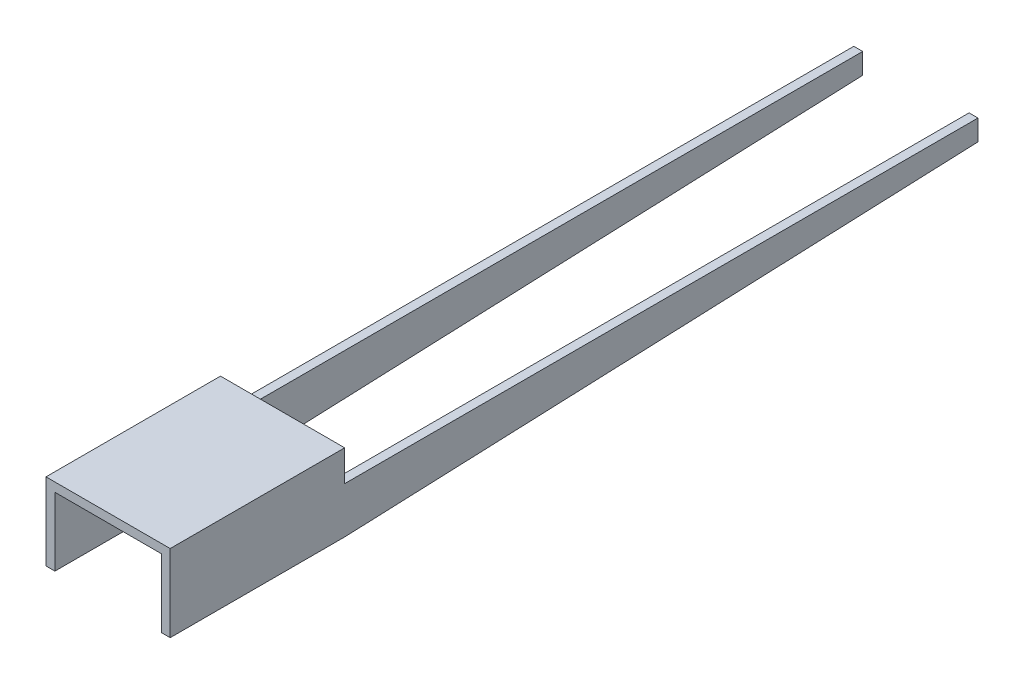
SolidWorks part; units mm, degrees
ref_plane "Front Plane" through (0, 0, 0) normal (0, 0, 1) x (1, 0, 0)
ref_plane "Top Plane" through (0, 0, 0) normal (0, 1, 0) x (1, 0, 0)
ref_plane "Right Plane" through (0, 0, 0) normal (1, 0, 0) x (0, 0, -1)
sketch "Sketch1" plane through (0, 0, 0) normal (0, 0, 1) x (1, 0, 0)
  line L0 (-30, 0) -> (-25.7, 0)
  line L5 (-25.7, 0) -> (-25.7, 20.7)
  line L6 (-25.7, 20.7) -> (25.7, 20.7)
  line L7 (25.7, 20.7) -> (25.7, 0)
  line L8 (25.7, 0) -> (30, 0)
  line L9 (30, 0) -> (30, 25)
  line L10 (30, 25) -> (-30, 25)
  line L11 (-30, 25) -> (-30, 0)
  point P9 (0, 20.7)
  dimension "D1" = 4.3
  dimension "D2" = 4.3
  dimension "D3" = 60
  dimension "D4" = 25
extrude "Boss-Extrude1" add sketch "Sketch1" along normal blind 390.3
sketch "Sketch2" plane through (30, 0, 0) normal (1, 0, 0) x (0, 0, -1)
  line L0 (-306, 0) -> (-306, -12.31) construction
  line L1 (-306, -12.31) -> (0, 0)
  line L2 (0, 0) -> (-390.3, 0)
  line L3 (-390.3, 0) -> (-390.3, -12.31)
  line L4 (-390.3, -12.31) -> (-306, -12.31)
  dimension "D1" = 306
  dimension "D2" = 12.31
extrude "Boss-Extrude2" add sketch "Sketch2" against normal blind 4.3
mirror "Mirror1" about plane through (0, 0, 0) normal (1, 0, 0) of "Boss-Extrude2"
sketch "Sketch3" plane through (0, 25, 0) normal (0, 1, 0) x (1, 0, 0)
  line L0 (-20.5205, 0) -> (20.5205, 0) construction
  line L1 (-4.3, 0) -> (4.3, 0)
  line L2 (-4.3, 0) -> (-4.3, -70)
  line L3 (-4.3, -70) -> (4.3, -70)
  line L4 (4.3, 0) -> (4.3, -70)
  line L5 (0, -20.5205) -> (0, 20.5205) construction
  point P6 (0, 0)
  dimension "D1" = 70
  dimension "D2" = 8.6
extrude "Cut-Extrude1" cut sketch "Sketch3" against normal blind 10
sketch "Sketch4" plane through (0, 25, 0) normal (0, 1, 0) x (1, 0, 0)
  line L0 (30, -390.3) -> (-30, -390.3) construction
  line L1 (-72.4089, 43.2578) -> (158.3943, 43.2578)
  line L2 (-72.4089, 43.2578) -> (-72.4089, -306)
  line L3 (-72.4089, -306) -> (158.3943, -306)
  line L4 (158.3943, 43.2578) -> (158.3943, -306)
  point P4 (158.3943, -311.0763)
  dimension "D1" = 84.3
extrude "Cut-Extrude2" cut sketch "Sketch4" against normal blind 15
